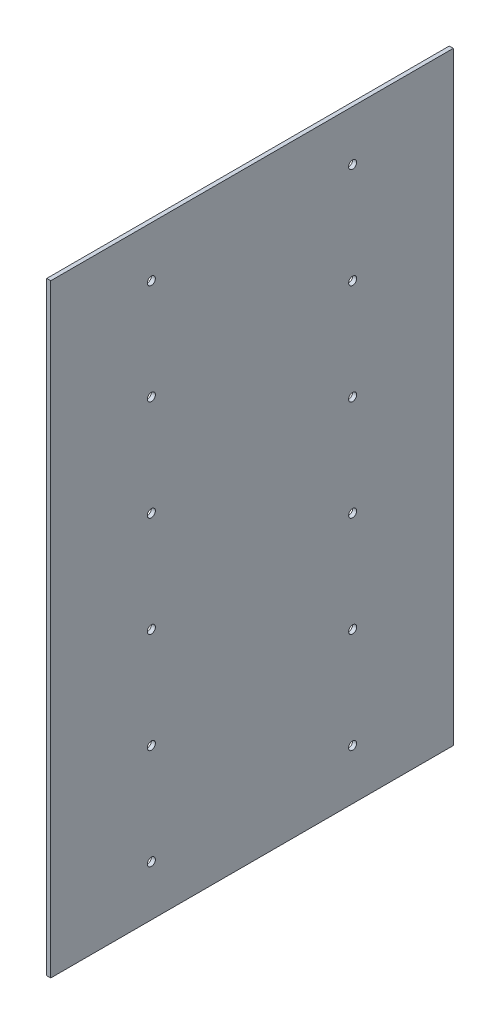
SolidWorks part; units mm, degrees
ref_plane "Спереди" through (0, 0, 0) normal (0, 0, 1) x (1, 0, 0)
ref_plane "Сверху" through (0, 0, 0) normal (0, 1, 0) x (1, 0, 0)
ref_plane "Справа" through (0, 0, 0) normal (1, 0, 0) x (0, 0, -1)
sketch "Эскиз1" plane through (0, 0, 0) normal (1, 0, 0) x (0, 0, -1)
  line L1 (-100, -150) -> (100, -150)
  line L2 (-100, -150) -> (-100, 150)
  line L3 (-100, 150) -> (100, 150)
  line L4 (100, -150) -> (100, 150)
  line L5 (-100, -150) -> (100, 150) construction
  line L6 (-100, 150) -> (100, -150) construction
  point P0 (0, 0)
  dimension "D1" = 200
  dimension "D2" = 300
extrude "Бобышка-Вытянуть1" add sketch "Эскиз1" along normal blind 2
sketch "Эскиз2" plane through (2, 0, 0) normal (1, 0, 0) x (0, 0, -1)
  line L0 (-100, 150) -> (-100, -150) construction
  line L1 (100, 150) -> (-100, 150) construction
  line L2 (-100, 0) -> (100, 0) construction
  line L3 (100, -150) -> (100, 150) construction
  line L4 (0, 150) -> (0, -150) construction
  line L5 (-100, -150) -> (100, -150) construction
  circle A0 centre (-50, 125) radius 2
  circle A1 centre (50, 125) radius 2
  circle A2 centre (50, -125) radius 2
  circle A3 centre (-50, -125) radius 2
  circle A4 centre (-50, 75) radius 2
  circle A5 centre (-50, 25) radius 2
  circle A6 centre (50, 25) radius 2
  circle A7 centre (50, 75) radius 2
  circle A8 centre (-50, -25) radius 2
  circle A9 centre (50, -25) radius 2
  circle A10 centre (50, -75) radius 2
  circle A11 centre (-50, -75) radius 2
  dimension "D1" = 100
  dimension "D2" = 4
  dimension "D5" = 50
  dimension "D3" = 50
  dimension "D4" = 25
  dimension "D6" = 50
extrude "Вырез-Вытянуть1" cut sketch "Эскиз2" against normal up to surface (2 mm away) up to face at (0, 0, 0)
